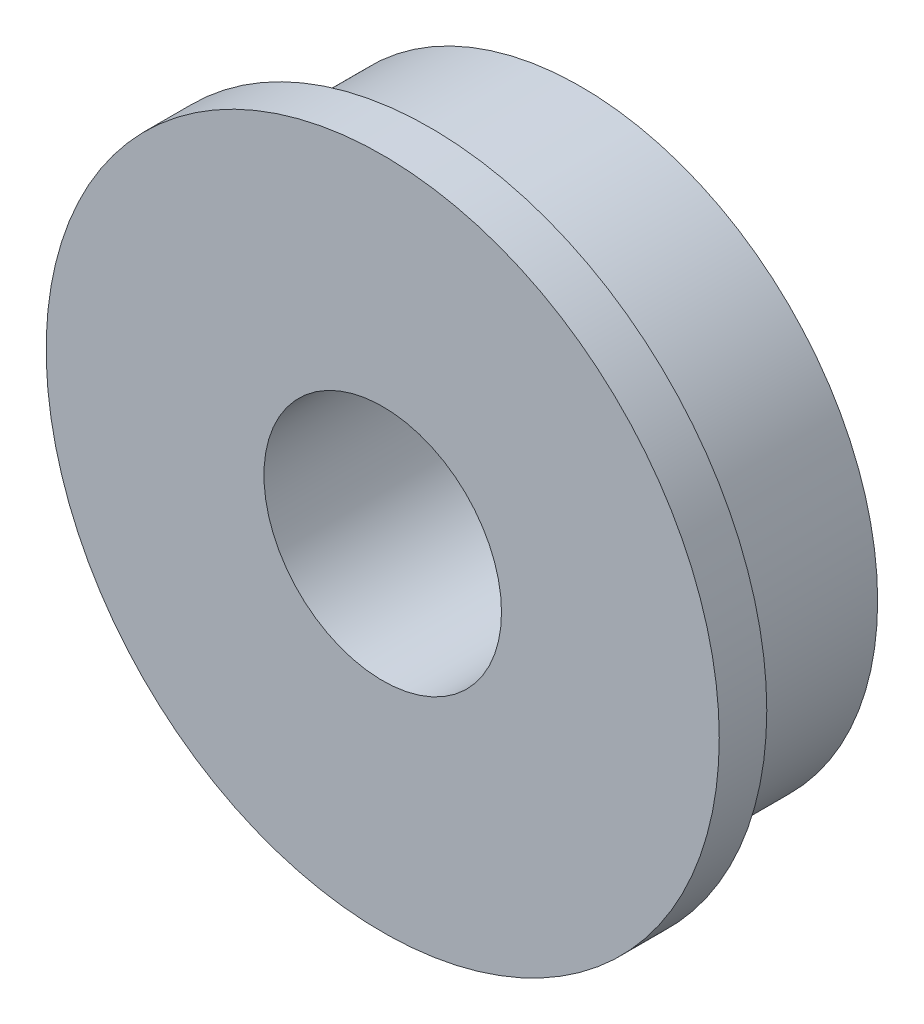
SolidWorks part; units mm, degrees
material "6系铝"
ref_plane "前视基准面" through (0, 0, 0) normal (0, 0, 1) x (1, 0, 0)
ref_plane "上视基准面" through (0, 0, 0) normal (0, 1, 0) x (1, 0, 0)
ref_plane "右视基准面" through (0, 0, 0) normal (1, 0, 0) x (0, 0, -1)
sketch "草图1" plane through (0, 0, 0) normal (0, 0, 1) x (1, 0, 0)
  circle A0 centre (0, 0) radius 3
  circle A1 centre (0, 0) radius 7.5
  dimension "D1" = 6
  dimension "D2" = 15
extrude "凸台-拉伸1" add sketch "草图1" along normal blind 5
sketch "草图2" plane through (0, 0, 5) normal (0, 0, 1) x (1, 0, 0)
  circle A0 centre (0, 0) radius 8.5
  circle A1 centre (0, 0) radius 7.5
  circle A2 centre (0, 0) radius 7.5
  dimension "D2" = 17
  dimension "D1" = 0
extrude "凸台-拉伸2" add sketch "草图2" against normal blind 1.2
